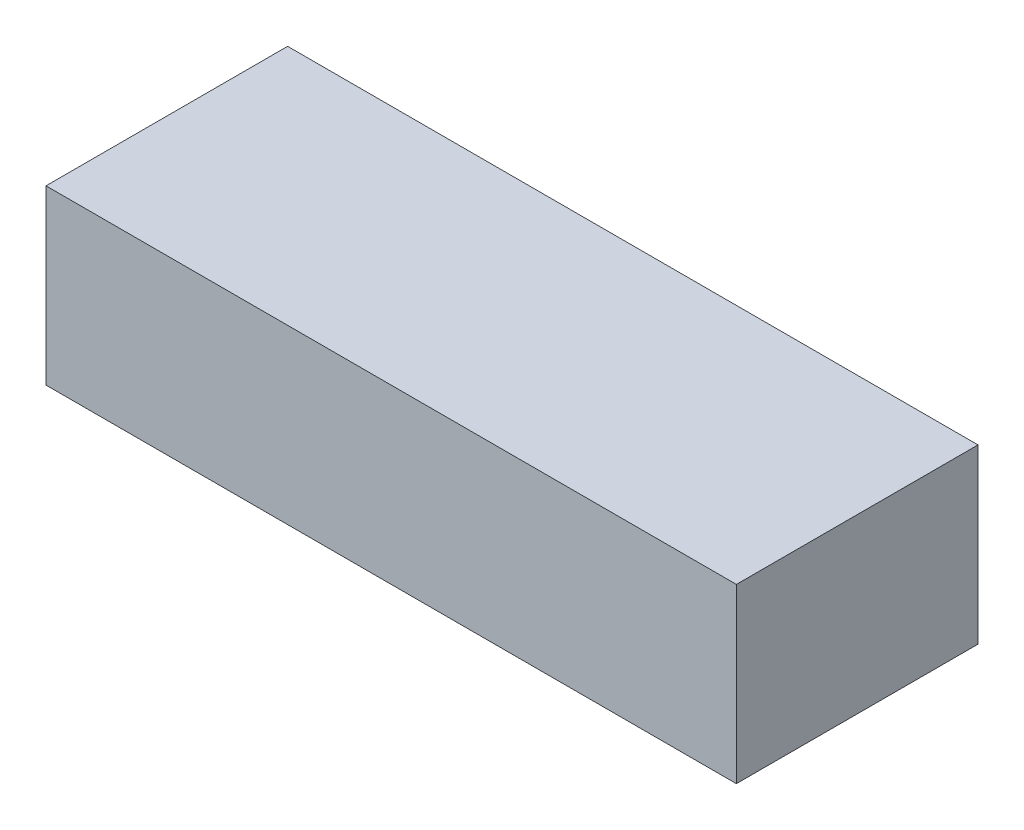
SolidWorks part; units mm, degrees
ref_plane "Front Plane" through (0, 0, 0) normal (0, 0, 1) x (1, 0, 0)
ref_plane "Top Plane" through (0, 0, 0) normal (0, 1, 0) x (1, 0, 0)
ref_plane "Right Plane" through (0, 0, 0) normal (1, 0, 0) x (0, 0, -1)
sketch "Sketch1" plane through (0, 0, 0) normal (0, 1, 0) x (1, 0, 0)
  line L1 (-50, 17.5) -> (50, 17.5)
  line L2 (-50, 17.5) -> (-50, -17.5)
  line L3 (-50, -17.5) -> (50, -17.5)
  line L4 (50, 17.5) -> (50, -17.5)
  line L5 (-50, 17.5) -> (50, -17.5) construction
  line L6 (-50, -17.5) -> (50, 17.5) construction
  point P0 (0, 0)
  dimension "D1" = 35
  dimension "D2" = 100
extrude "Boss-Extrude1" add sketch "Sketch1" along normal blind 25
